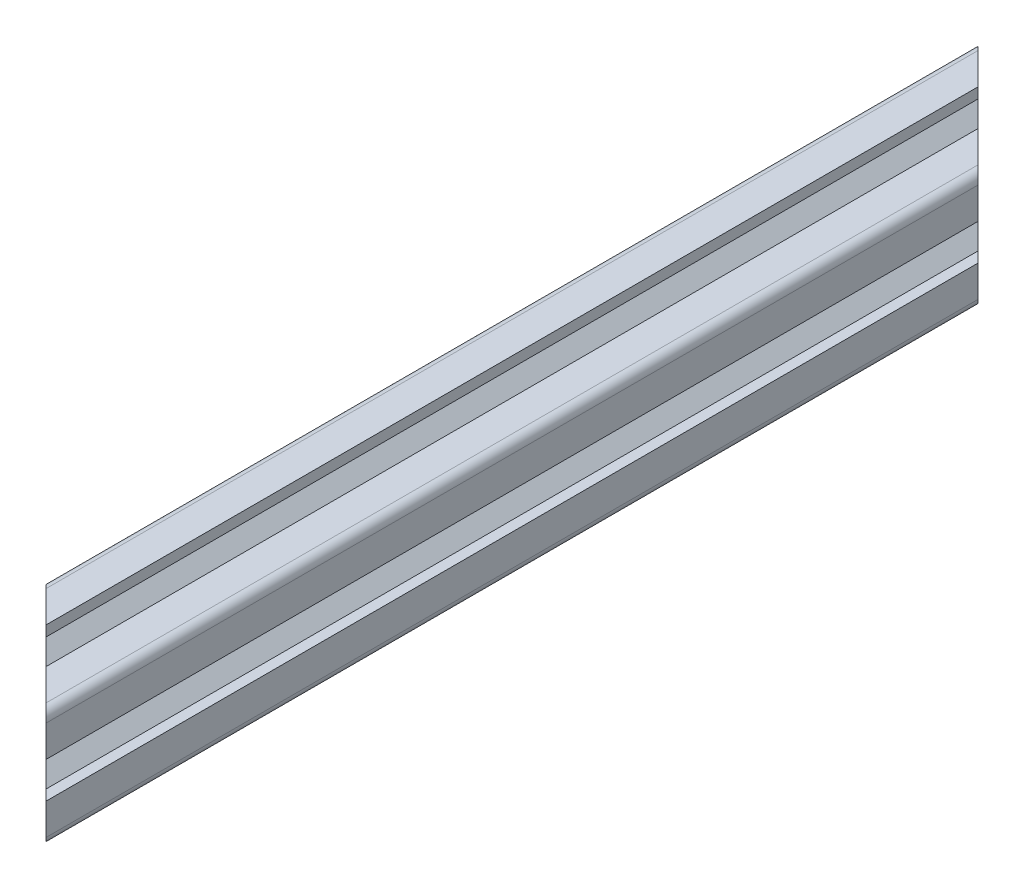
SolidWorks part; units mm, degrees
ref_plane "前视基准面" through (0, 0, 0) normal (0, 0, 1) x (1, 0, 0)
ref_plane "上视基准面" through (0, 0, 0) normal (0, 1, 0) x (1, 0, 0)
ref_plane "右视基准面" through (0, 0, 0) normal (1, 0, 0) x (0, 0, -1)
sketch "草图1" plane through (0, 0, 0) normal (0, 0, 1) x (1, 0, 0)
  line L0 (-10, -3.1) -> (-8.2, -3.1)
  line L1 (-8.5, 10) -> (8.5, 10)
  line L2 (-10, 8.5) -> (-10, -8.5)
  line L3 (-8.5, -10) -> (8.5, -10)
  line L4 (10, 8.5) -> (10, -8.5)
  line L5 (-10, 10) -> (10, -10) construction
  line L6 (-10, -10) -> (10, 10) construction
  line L7 (-3.0541, 3.1) -> (3.0541, 3.1)
  line L8 (-3.0541, 3.1) -> (-3.0541, -3.1)
  line L9 (-3.0541, -3.1) -> (3.0541, -3.1)
  line L10 (3.0541, 3.1) -> (3.0541, -3.1)
  line L11 (-3.0541, 3.1) -> (3.0541, -3.1) construction
  line L12 (-3.0541, -3.1) -> (3.0541, 3.1) construction
  line L13 (-8.2, -3.1) -> (-8.2, -5.5)
  line L14 (-8.2, -5.5) -> (-6.3971, -5.5)
  line L15 (-6.3971, -5.5) -> (-3.0541, -2.1571)
  line L16 (-5.5, 6.3971) -> (-2.1571, 3.0541)
  line L17 (-5.5, 8.2) -> (-5.5, 6.3971)
  line L18 (-3.1, 8.2) -> (-5.5, 8.2)
  line L19 (-3.1, 10) -> (-3.1, 8.2)
  line L20 (6.3971, 5.5) -> (3.0541, 2.1571)
  line L21 (8.2, 5.5) -> (6.3971, 5.5)
  line L22 (8.2, 3.1) -> (8.2, 5.5)
  line L23 (10, 3.1) -> (8.2, 3.1)
  line L24 (5.5, -6.3971) -> (2.1571, -3.0541)
  line L25 (5.5, -8.2) -> (5.5, -6.3971)
  line L26 (3.1, -8.2) -> (5.5, -8.2)
  line L27 (3.1, -10) -> (3.1, -8.2)
  line L28 (-3.1, -10) -> (-3.1, -8.2)
  line L29 (-3.1, -8.2) -> (-5.5, -8.2)
  line L30 (-5.5, -8.2) -> (-5.5, -6.3971)
  line L31 (-5.5, -6.3971) -> (-2.1571, -3.0541)
  line L32 (-8.2, 5.5) -> (-6.3971, 5.5)
  line L33 (-6.3971, 5.5) -> (-3.0541, 2.1571)
  line L34 (-8.2, 3.1) -> (-8.2, 5.5)
  line L35 (-10, 3.1) -> (-8.2, 3.1)
  line L36 (5.5, 8.2) -> (5.5, 6.3971)
  line L37 (5.5, 6.3971) -> (2.1571, 3.0541)
  line L38 (3.1, 8.2) -> (5.5, 8.2)
  line L39 (3.1, 10) -> (3.1, 8.2)
  line L40 (8.2, -5.5) -> (6.3971, -5.5)
  line L41 (6.3971, -5.5) -> (3.0541, -2.1571)
  line L42 (8.2, -3.1) -> (8.2, -5.5)
  line L43 (10, -3.1) -> (8.2, -3.1)
  circle A0 centre (0, 0) radius 2.5
  arc A1 (-10, 8.5) -> (-8.5, 10) centre (-8.5, 8.5) cw
  arc A2 (-10, -8.5) -> (-8.5, -10) centre (-8.5, -8.5) ccw
  arc A3 (8.5, 10) -> (10, 8.5) centre (8.5, 8.5) cw
  arc A4 (10, -8.5) -> (8.5, -10) centre (8.5, -8.5) cw
  point P0 (0, 0)
  point P20 (0, 0)
  point P26 (0, 0)
  point P32 (0, 0)
  point P38 (0, 0)
  point P60 (0, 0)
  dimension "D1" = 4
  dimension "D3" = 1.5
  dimension "D4" = 1.5
  dimension "D5" = 1.5
  dimension "D2" = 4
extrude "凸台-拉伸1" add sketch "草图1" along normal blind 180
sketch "草图2" plane through (0, 10, 0) normal (0, 1, 0) x (1, 0, 0)
  line L0 (-10, 0) -> (10, 0)
  line L1 (10, 0) -> (10, -20)
  line L2 (10, -180) -> (10, 0) construction
  line L3 (10, -20) -> (-10, 0)
  line L4 (-10, -180) -> (-10, -160)
  line L5 (-10, -180) -> (-10, 0) construction
  line L6 (-10, -160) -> (10, -180)
  line L7 (10, -180) -> (-10, -180)
extrude "切除-拉伸1" cut sketch "草图2" against normal through all
